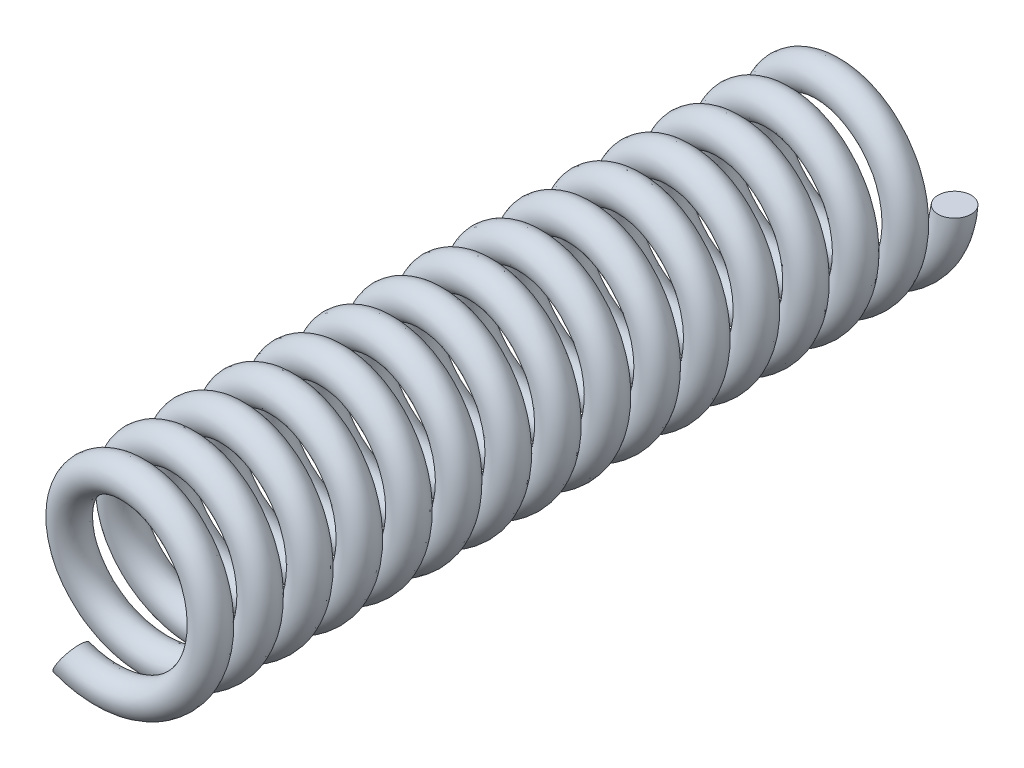
SolidWorks part; units mm, degrees
ref_plane "Front Plane" through (0, 0, 0) normal (0, 0, 1) x (1, 0, 0)
ref_plane "Top Plane" through (0, 0, 0) normal (0, 1, 0) x (1, 0, 0)
ref_plane "Right Plane" through (0, 0, 0) normal (1, 0, 0) x (0, 0, -1)
sketch "Sketch1" plane through (0, 0, 0) normal (0, 0, 1) x (1, 0, 0)
  circle A0 centre (0, 0) radius 2.5
  dimension "D1" = 5
curve "Helix/Spiral1" pitch 1.5 height 22.995 turns 15.33
sketch "Sketch2" plane through (0, 0, 0) normal (0, 1, 0) x (1, 0, 0)
  circle A0 centre (2.5, 0) radius 0.5
  spline S0 degree 3 poles (2.5, 0) (2.5, -0.0311) (2.3695, -0.0939) (1.8123, -0.1877) (0.9785, -0.2816) (-0.0046, -0.3754) (-0.987, -0.4693) (-1.8188, -0.5631) (-2.373, -0.657) (-2.5652, -0.7509) (-2.366, -0.8447) (-1.8057, -0.9386) (-0.97, -1.0324) (0.0138, -1.1263) (0.9955, -1.2201) (1.8253, -1.314) (2.3765, -1.4079) (2.5652, -1.5017) (2.3624, -1.5956) (1.7992, -1.6894) (0.9614, -1.7833) (-0.023, -1.8771) (-1.004, -1.971) (-1.8317, -2.0649) (-2.38, -2.1587) (-2.5651, -2.2526) (-2.3588, -2.3464) (-1.7926, -2.4403) (-0.9529, -2.5341) (0.0322, -2.628) (1.0124, -2.7219) (1.8382, -2.8157) (2.3834, -2.9096) (2.565, -3.0034) (2.3552, -3.0973) (1.786, -3.1911) (0.9443, -3.285) (-0.0414, -3.3789) (-1.0209, -3.4727) (-1.8446, -3.5666) (-2.3868, -3.6604) (-2.5648, -3.7543) (-2.3515, -3.8481) (-1.7794, -3.942) (-0.9358, -4.0359) (0.0507, -4.1297) (1.0293, -4.2236) (1.851, -4.3174) (2.3901, -4.4113) (2.5646, -4.5051) (2.3478, -4.599) (1.7727, -4.6929) (0.9272, -4.7867) (-0.0599, -4.8806) (-1.0378, -4.9744) (-1.8573, -5.0683) (-2.3935, -5.1621) (-2.5644, -5.256) (-2.3441, -5.3499) (-1.7661, -5.4437) (-0.9186, -5.5376) (0.0691, -5.6314) (1.0462, -5.7253) (1.8637, -5.8191) (2.3968, -5.913) (2.5642, -6.0069) (2.3403, -6.1007) (1.7594, -6.1946) (0.91, -6.2884) (-0.0783, -6.3823) (-1.0546, -6.4761) (-1.87, -6.57) (-2.4, -6.6639) (-2.5639, -6.7577) (-2.3365, -6.8516) (-1.7527, -6.9454) (-0.9014, -7.0393) (0.0875, -7.1331) (1.063, -7.227) (1.8763, -7.3209) (2.4033, -7.4147) (2.5636, -7.5086) (2.3327, -7.6024) (1.7459, -7.6963) (0.8927, -7.7901) (-0.0967, -7.884) (-1.0713, -7.9779) (-1.8825, -8.0717) (-2.4065, -8.1656) (-2.5632, -8.2594) (-2.3289, -8.3533) (-1.7392, -8.4471) (-0.8841, -8.541) (0.1059, -8.6349) (1.0797, -8.7287) (1.8888, -8.8226) (2.4097, -8.9164) (2.5629, -9.0103) (2.325, -9.1041) (1.7324, -9.198) (0.8754, -9.2919) (-0.1151, -9.3857) (-1.0881, -9.4796) (-1.895, -9.5734) (-2.4128, -9.6673) (-2.5624, -9.7611) (-2.3211, -9.855) (-1.7256, -9.9489) (-0.8668, -10.0427) (0.1243, -10.1366) (1.0964, -10.2304) (1.9012, -10.3243) (2.4159, -10.4181) (2.562, -10.512) (2.3172, -10.6059) (1.7188, -10.6997) (0.8581, -10.7936) (-0.1335, -10.8874) (-1.1047, -10.9813) (-1.9074, -11.0751) (-2.419, -11.169) (-2.5615, -11.2629) (-2.3132, -11.3567) (-1.7119, -11.4506) (-0.8494, -11.5444) (0.1427, -11.6383) (1.113, -11.7321) (1.9135, -11.826) (2.422, -11.9199) (2.561, -12.0137) (2.3092, -12.1076) (1.705, -12.2014) (0.8407, -12.2953) (-0.1519, -12.3891) (-1.1213, -12.483) (-1.9196, -12.5769) (-2.4251, -12.6707) (-2.5605, -12.7646) (-2.3052, -12.8584) (-1.6981, -12.9523) (-0.832, -13.0461) (0.1611, -13.14) (1.1296, -13.2339) (1.9257, -13.3277) (2.428, -13.4216) (2.5599, -13.5154) (2.3011, -13.6093) (1.6912, -13.7031) (0.8233, -13.797) (-0.1703, -13.8909) (-1.1378, -13.9847) (-1.9318, -14.0786) (-2.431, -14.1724) (-2.5593, -14.2663) (-2.297, -14.3601) (-1.6843, -14.454) (-0.8146, -14.5479) (0.1795, -14.6417) (1.1461, -14.7356) (1.9379, -14.8294) (2.4339, -14.9233) (2.5586, -15.0171) (2.2929, -15.111) (1.6773, -15.2049) (0.8058, -15.2987) (-0.1886, -15.3926) (-1.1543, -15.4864) (-1.9439, -15.5803) (-2.4368, -15.6741) (-2.5579, -15.768) (-2.2888, -15.8619) (-1.6704, -15.9557) (-0.7971, -16.0496) (0.1978, -16.1434) (1.1625, -16.2373) (1.9499, -16.3311) (2.4397, -16.425) (2.5572, -16.5189) (2.2846, -16.6127) (1.6634, -16.7066) (0.7883, -16.8004) (-0.207, -16.8943) (-1.1707, -16.9881) (-1.9558, -17.082) (-2.4425, -17.1759) (-2.5565, -17.2697) (-2.2804, -17.3636) (-1.6563, -17.4574) (-0.7796, -17.5513) (0.2162, -17.6451) (1.1789, -17.739) (1.9618, -17.8329) (2.4453, -17.9267) (2.5557, -18.0206) (2.2762, -18.1144) (1.6493, -18.2083) (0.7708, -18.3021) (-0.2254, -18.396) (-1.1871, -18.4899) (-1.9677, -18.5837) (-2.4481, -18.6776) (-2.5549, -18.7714) (-2.2719, -18.8653) (-1.6422, -18.9591) (-0.762, -19.053) (0.2345, -19.1469) (1.1953, -19.2407) (1.9736, -19.3346) (2.4508, -19.4284) (2.5541, -19.5223) (2.2676, -19.6161) (1.6351, -19.71) (0.7532, -19.8039) (-0.2437, -19.8977) (-1.2034, -19.9916) (-1.9795, -20.0854) (-2.4535, -20.1793) (-2.5532, -20.2731) (-2.2633, -20.367) (-1.628, -20.4609) (-0.7444, -20.5547) (0.2529, -20.6486) (1.2115, -20.7424) (1.9853, -20.8363) (2.4562, -20.9301) (2.5523, -21.024) (2.2589, -21.1179) (1.6209, -21.2117) (0.7356, -21.3056) (-0.262, -21.3994) (-1.2196, -21.4933) (-1.9911, -21.5871) (-2.4588, -21.681) (-2.5513, -21.7749) (-2.2546, -21.8687) (-1.6138, -21.9626) (-0.7267, -22.0564) (0.2712, -22.1503) (1.2277, -22.2441) (1.9969, -22.338) (2.4614, -22.4319) (2.5504, -22.5257) (2.2501, -22.6196) (1.6066, -22.7134) (0.7177, -22.8073) (-0.2795, -22.9011) (-0.9191, -22.9639) (-1.2044, -22.995) knots 0 0 0 0 0.004082 0.008163 0.012245 0.016327 0.020408 0.02449 0.028571 0.032653 0.036735 0.040816 0.044898 0.04898 0.053061 0.057143 0.061224 0.065306 0.069388 0.073469 0.077551 0.081633 0.085714 0.089796 0.093878 0.097959 0.102041 0.106122 0.110204 0.114286 0.118367 0.122449 0.126531 0.130612 0.134694 0.138776 0.142857 0.146939 0.15102 0.155102 0.159184 0.163265 0.167347 0.171429 0.17551 0.179592 0.183673 0.187755 0.191837 0.195918 0.2 0.204082 0.208163 0.212245 0.216327 0.220408 0.22449 0.228571 0.232653 0.236735 0.240816 0.244898 0.24898 0.253061 0.257143 0.261224 0.265306 0.269388 0.273469 0.277551 0.281633 0.285714 0.289796 0.293878 0.297959 0.302041 0.306122 0.310204 0.314286 0.318367 0.322449 0.326531 0.330612 0.334694 0.338776 0.342857 0.346939 0.35102 0.355102 0.359184 0.363265 0.367347 0.371429 0.37551 0.379592 0.383673 0.387755 0.391837 0.395918 0.4 0.404082 0.408163 0.412245 0.416327 0.420408 0.42449 0.428571 0.432653 0.436735 0.440816 0.444898 0.44898 0.453061 0.457143 0.461224 0.465306 0.469388 0.473469 0.477551 0.481633 0.485714 0.489796 0.493878 0.497959 0.502041 0.506122 0.510204 0.514286 0.518367 0.522449 0.526531 0.530612 0.534694 0.538776 0.542857 0.546939 0.55102 0.555102 0.559184 0.563265 0.567347 0.571429 0.57551 0.579592 0.583673 0.587755 0.591837 0.595918 0.6 0.604082 0.608163 0.612245 0.616327 0.620408 0.62449 0.628571 0.632653 0.636735 0.640816 0.644898 0.64898 0.653061 0.657143 0.661224 0.665306 0.669388 0.673469 0.677551 0.681633 0.685714 0.689796 0.693878 0.697959 0.702041 0.706122 0.710204 0.714286 0.718367 0.722449 0.726531 0.730612 0.734694 0.738776 0.742857 0.746939 0.75102 0.755102 0.759184 0.763265 0.767347 0.771429 0.77551 0.779592 0.783673 0.787755 0.791837 0.795918 0.8 0.804082 0.808163 0.812245 0.816327 0.820408 0.82449 0.828571 0.832653 0.836735 0.840816 0.844898 0.84898 0.853061 0.857143 0.861224 0.865306 0.869388 0.873469 0.877551 0.881633 0.885714 0.889796 0.893878 0.897959 0.902041 0.906122 0.910204 0.914286 0.918367 0.922449 0.926531 0.930612 0.934694 0.938776 0.942857 0.946939 0.95102 0.955102 0.959184 0.963265 0.967347 0.971429 0.97551 0.979592 0.983673 0.987755 0.991837 0.995918 1 1 1 1 construction
  dimension "D1" = 1
sweep "Sweep1" add profiles "Sketch2" path "Helix/Spiral1"
